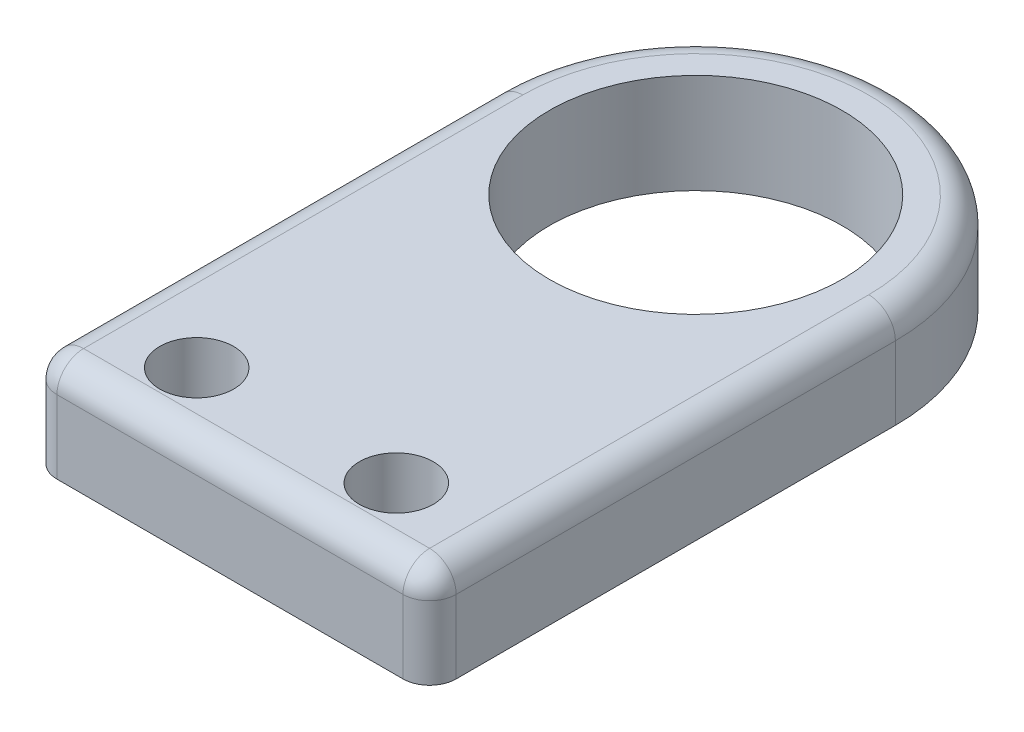
SolidWorks part; units mm, degrees
material "ABS"
ref_plane "Front" through (0, 0, 0) normal (0, 0, 1) x (1, 0, 0)
ref_plane "Top" through (0, 0, 0) normal (0, 1, 0) x (1, 0, 0)
ref_plane "Right" through (0, 0, 0) normal (1, 0, 0) x (0, 0, -1)
sketch "Sketch1" plane through (0, 0, 0) normal (0, 1, 0) x (1, 0, 0)
  line L1 (-15, 0) -> (15, 0)
  line L2 (-15, 0) -> (-15, 35)
  line L4 (15, 0) -> (15, 35)
  circle A0 centre (0, 35) radius 11
  arc A1 (-15, 35) -> (15, 35) centre (0, 35) cw
  point P4 (0, 0)
  dimension "D3" = 22
  dimension "D1" = 30
  dimension "D4" = 35
extrude "Boss-Extrude1" add sketch "Sketch1" along normal blind 7.5
hole_wizard "CBORE for #2 Binding Head Machine Screw1" positions "Sketch3" profile "Sketch4" counterbore size "#2" standard "ANSI Inch"
sketch "Sketch3" plane through (0, 7.5, 0) normal (0, 1, 0) x (1, 0, 0)
  line L0 (-7.5, 5) -> (7.5, 5) construction
  line L1 (0, 5) -> (0, 0) construction
  line L2 (-15, 0) -> (15, 0) construction
  point P0 (-7.5, 5)
  point P2 (7.5, 5)
  dimension "D1" = 5
  dimension "D2" = 15
sketch "Sketch4" plane through (-7.5, 7.5, -5) normal (1, 0, 0) x (0, 0, 1)
  line L0 (0, 0) -> (0, 10.7326)
  line L1 (0, 10.7326) -> (1.2192, 10)
  line L2 (1.2192, 10) -> (1.2192, 5)
  line L3 (1.2192, 5) -> (2.7788, 5)
  line L4 (2.7788, 5) -> (2.7788, 0)
  line L5 (2.7788, 0) -> (0, 0)
  line L10 (0, 10.7326) -> (-1.2192, 10) construction
  line L11 (0, -6.35) -> (0, 107.95) construction
  dimension "Hole Dia." = 2.4384
  dimension "Hole Depth" = 10
  dimension "C'Bore Dia." = 5.5575
  dimension "C'Bore Depth" = 5
  dimension "Drill Angle" = 118
fillet "Fillet1" radius 2 6 edges at (-15, 7.5, -17.5) (0, 7.5, -50) (0, 7.5, 0) (15, 7.5, -17.5) (-15, 3.75, 0) (15, 3.75, 0)
